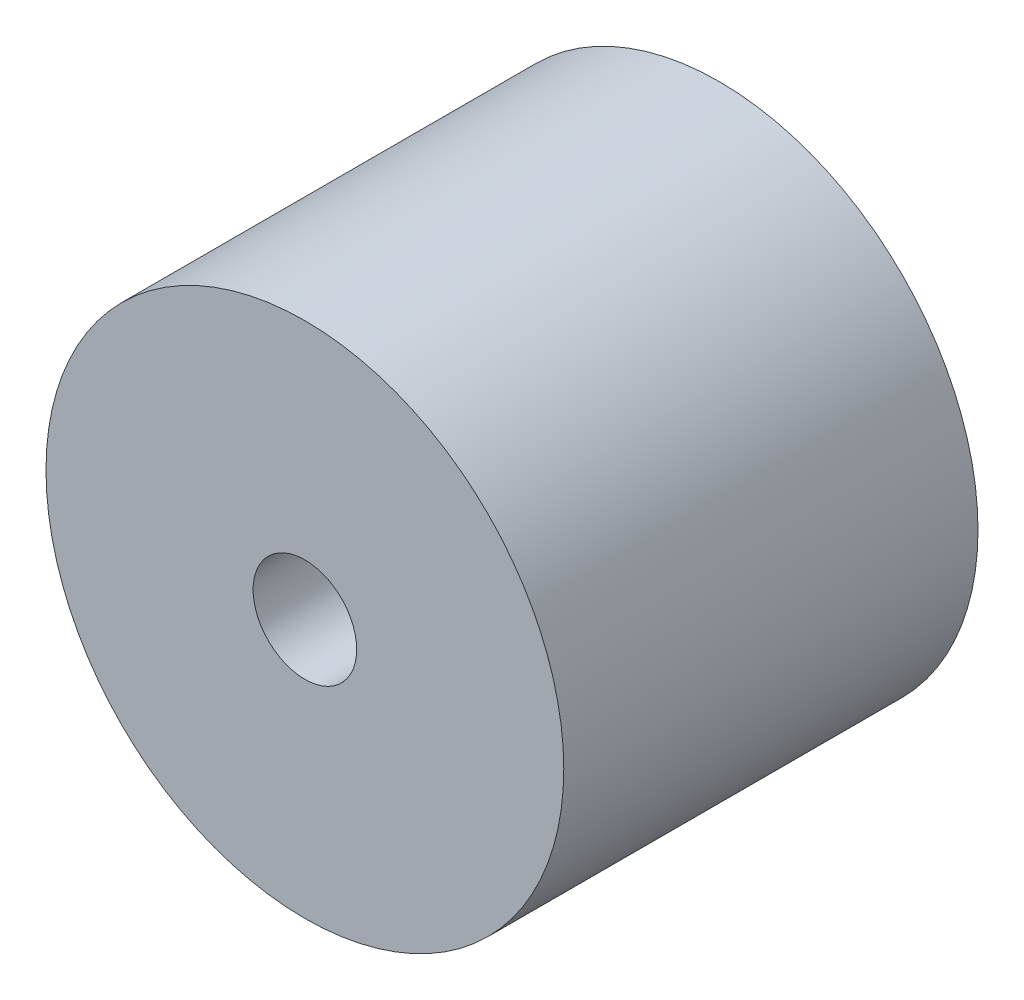
SolidWorks part; units mm, degrees
ref_plane "Front Plane" through (0, 0, 0) normal (0, 0, 1) x (1, 0, 0)
ref_plane "Top Plane" through (0, 0, 0) normal (0, 1, 0) x (1, 0, 0)
ref_plane "Right Plane" through (0, 0, 0) normal (1, 0, 0) x (0, 0, -1)
sketch "Sketch1" plane through (0, 0, 0) normal (0, 0, 1) x (1, 0, 0)
  circle A0 centre (0, 0) radius 4
  circle A1 centre (0, 0) radius 20
  dimension "D1" = 40
  dimension "D2" = 8
extrude "Boss-Extrude1" add sketch "Sketch1" along normal mid plane 32
